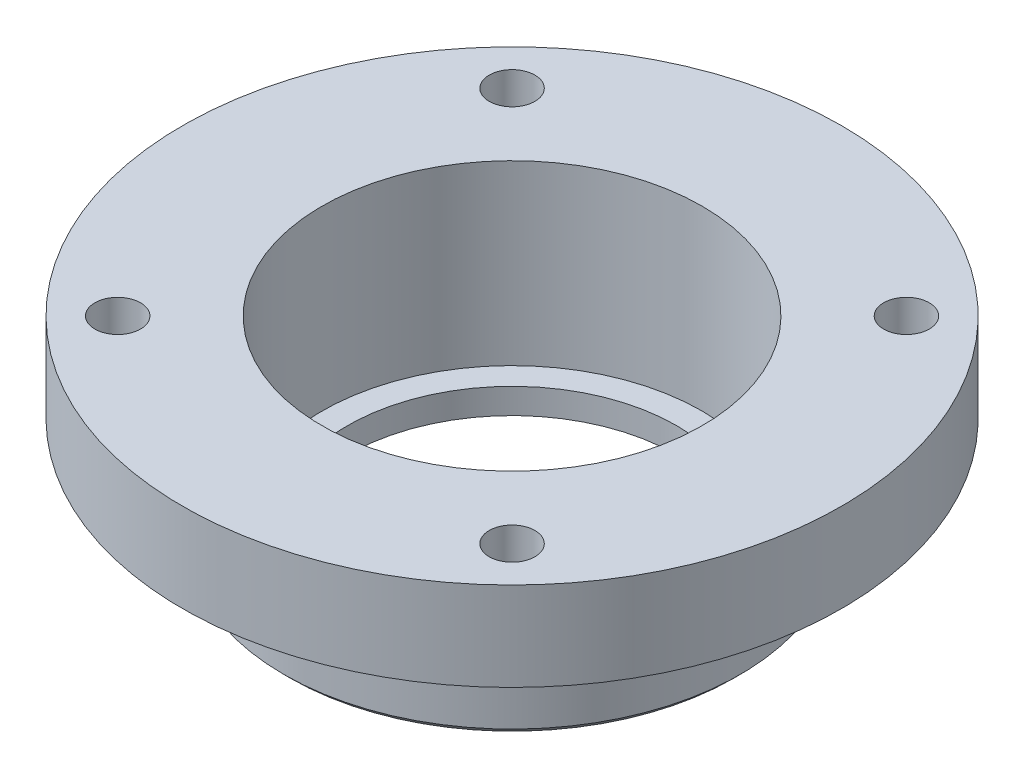
SolidWorks part; units mm, degrees
ref_plane "Спереди" through (0, 0, 0) normal (0, 0, 1) x (1, 0, 0)
ref_plane "Сверху" through (0, 0, 0) normal (0, 1, 0) x (1, 0, 0)
ref_plane "Справа" through (0, 0, 0) normal (1, 0, 0) x (0, 0, -1)
sketch "Эскиз1" plane through (0, 0, 0) normal (0, 0, 1) x (1, 0, 0)
  line L0 (0, 0) -> (0, 8.0722) construction
  line L1 (-15, 2) -> (-15, 16)
  line L2 (-15, 16) -> (-26, 16)
  line L3 (-26, 16) -> (-26, 9)
  line L4 (-26, 9) -> (-18, 9)
  line L5 (-18, 9) -> (-18, 0)
  line L6 (-18, 0) -> (-13, 0)
  line L7 (-13, 0) -> (-13, 2)
  line L8 (-13, 2) -> (-15, 2)
  line L12 (-15, 15.4) -> (15, 15.4) construction
  line L13 (-15, 15.4) -> (15, 15.4) construction
  line L14 (14.4, 16) -> (-14.4, 16) construction
  dimension "D1" = 2
  dimension "D2" = 3
  dimension "D3" = 8
  dimension "D4" = 30
  dimension "D5" = 30
  dimension "D6" = 2
  dimension "D7" = 7
revolve "Повернуть1" add sketch "Эскиз1" angle 360 about L0
chamfer "Фаска1" distance 0.5 angle 45 1 edges at (0, 0, -18)
hole_wizard "Отверстие с зазором M31" positions "Эскиз2" profile "Эскиз3" hole size "M3" standard "DIN" end condition up to next
sketch "Эскиз2" plane through (0, 16, 0) normal (0, 1, 0) x (1, 0, 0)
  line L1 (12.7279, -12.7279) -> (18.3848, -18.3848) construction
  line L3 (0, 0) -> (50000, 0) construction
  circle A1 centre (0, 0) radius 26 construction
  circle A2 centre (0, 0) radius 18 construction
  circle A3 centre (0, 0) radius 26 construction
  circle A4 centre (0, 0) radius 18 construction
  circle A5 centre (0, 0) radius 26 construction
  point P39 (15.5563, -15.5563)
  dimension "D1" = 45
sketch "Эскиз3" plane through (15.5563, 16, 15.5563) normal (1, 0, 0) x (0, 0, 1)
  line L0 (0, 0) -> (0, 7)
  line L1 (0, 7) -> (1.8, 7)
  line L2 (1.8, 7) -> (1.8, 0)
  line L5 (1.8, 0) -> (0, 0)
  line L11 (0, -6.35) -> (0, 107.95) construction
  dimension "Диаметр сквозного отверстия" = 3.6
  dimension "Глубина сквозного отверстия" = 7
pattern_circular "Круговой массив1" count 4 over 360 about axis through (0, 0, 0) along (0, 1, 0) of "Отверстие с зазором M31"
equation "\"D5@Эскиз1\"=\"D4@Эскиз1\""
